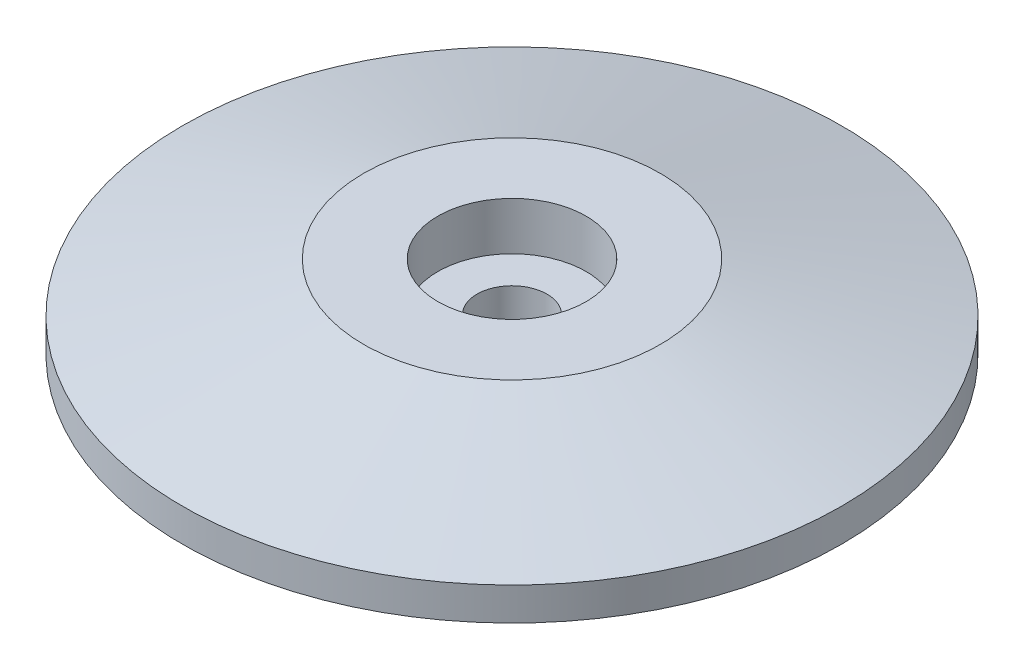
SolidWorks part; units mm, degrees
ref_plane "Front" through (0, 0, 0) normal (0, 0, 1) x (1, 0, 0)
ref_plane "Top" through (0, 0, 0) normal (0, 1, 0) x (1, 0, 0)
ref_plane "Right" through (0, 0, 0) normal (1, 0, 0) x (0, 0, -1)
sketch "Sketch1" plane through (0, 0, 0) normal (0, 0, 1) x (1, 0, 0)
  line L0 (0, 0) -> (63.5, 0)
  line L1 (63.5, 0) -> (63.5, 6.35)
  line L2 (63.5, 6.35) -> (28.575, 15.875)
  line L3 (28.575, 15.875) -> (0, 15.875)
  line L4 (0, 15.875) -> (0, 0) construction
  line L5 (0, 0) -> (0, 15.875)
  dimension "MainOD" = 127
  dimension "D2" = 57.15
  dimension "D3" = 15.875
  dimension "D4" = 6.35
revolve "Base-Revolve" add sketch "Sketch1" angle 360 about L4
sketch "Sketch2" plane through (0, 0, 0) normal (0, 0, 1) x (1, 0, 0)
  line L0 (-63.5, 0) -> (63.5, 0) construction
  line L1 (26.9875, 0) -> (31.75, 0)
  line L2 (26.9875, 0) -> (26.9875, 3.175)
  line L3 (26.9875, 3.175) -> (31.75, 3.175)
  line L4 (31.75, 0) -> (31.75, 3.175)
  line L5 (0, 0) -> (0, 32.6765) construction
  dimension "Groove_OD" = 63.5
  dimension "Groove_ID" = 53.975
  dimension "Groove_Depth" = 3.175
revolve "Groove" cut sketch "Sketch2" angle 360 about L5
hole_wizard "CBORE for 1/2 Hex Head Bolt1" positions "Sketch4" profile "Sketch3" counterbore size "1/2" standard "Ansi Inch" end condition through all
sketch "Sketch4" plane through (0, 15.875, 0) normal (0, 1, 0) x (-1, 0, 0)
  circle A0 centre (0, 0) radius 28.575 construction
  point P0 (0, 0)
sketch "Sketch3" plane through (0, 15.875, 0) normal (1, 0, 0) x (0, 0, 1)
  line L0 (0, 0) -> (0, 15.875)
  line L1 (0, 15.875) -> (6.7462, 15.875)
  line L3 (6.7462, 15.875) -> (6.7462, 9.2456)
  line L4 (6.7462, 9.2456) -> (14.2875, 9.2456)
  line L5 (14.2875, 9.2456) -> (14.2875, 0)
  line L7 (14.2875, 0) -> (0, 0)
  line L11 (0, -6.35) -> (0, 107.95) construction
  dimension "Thru Hole Dia." = 13.4925
  dimension "Thru Hole Depth" = 15.875
  dimension "C'Bore Dia." = 28.575
  dimension "C'Bore Depth" = 9.2456
